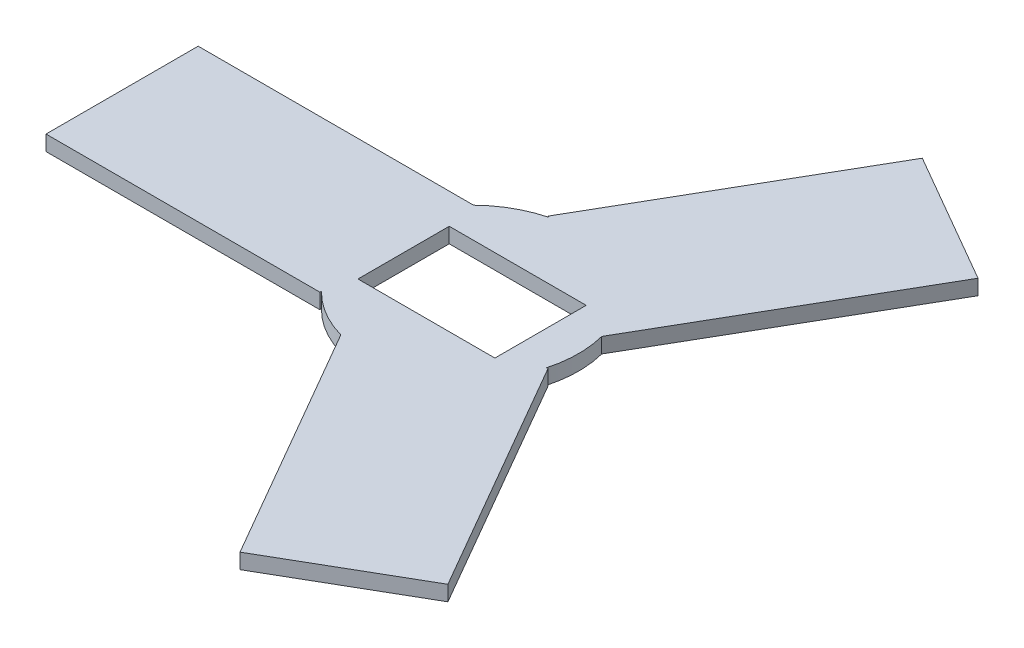
SolidWorks part; units mm, degrees
ref_plane "Plan de face" through (0, 0, 0) normal (0, 0, 1) x (1, 0, 0)
ref_plane "Plan de dessus" through (0, 0, 0) normal (0, 1, 0) x (1, 0, 0)
ref_plane "Plan de droite" through (0, 0, 0) normal (1, 0, 0) x (0, 0, -1)
sketch "Esquisse3" plane through (0, 0, 0) normal (0, 1, 0) x (1, 0, 0)
  line L0 (-150.1573, 0) -> (189.6273, 0) construction
  line L1 (-83.8395, -145.9242) -> (87.7229, 151.2306) construction
  line L2 (-78.0725, 135.2255) -> (117.7517, -203.9519) construction
  line L3 (-125, 131.2995) -> (-125, -153.5705) construction
  line L4 (-25, -25) -> (-115, -25)
  line L6 (-25, 25) -> (-24.4949, 25)
  line L7 (-115, -25) -> (-115, 25)
  line L8 (-25, -25) -> (-115, 25) construction
  line L9 (-25, 25) -> (-115, -25) construction
  line L10 (-24.4949, 25) -> (-115, 25)
  line L11 (33.8981, 8.7132) -> (79.1506, 87.0929)
  line L12 (35.8494, 112.0929) -> (79.1506, 87.0929)
  line L13 (-9.1506, 34.1506) -> (35.8494, 112.0929)
  line L14 (-9.4032, -33.7132) -> (35.8494, -112.0929)
  line L15 (79.1506, -87.0929) -> (35.8494, -112.0929)
  line L16 (34.1506, -9.1506) -> (79.1506, -87.0929)
  line L17 (-24.4949, 25) -> (-25, -25)
  line L18 (-9.1506, 34.1506) -> (33.8981, 8.7132)
  line L19 (-9.4032, -33.7132) -> (34.1506, -9.1506)
  circle A0 centre (0, 0) radius 125
  circle A1 centre (0, 0) radius 35
  circle A2 centre (0, 0) radius 125
  circle A3 centre (0, 0) radius 125
  point P9 (-70, 0)
  point P32 (0, 0)
  dimension "D1" = 250
  dimension "D4" = 70
  dimension "D2" = 120
  dimension "D3" = 120
  dimension "D5" = 10
  dimension "D6" = 50
  dimension "D7" = 90
  dimension "D8" = 3
extrude "Boss.-Extru.3" add sketch "Esquisse3" along normal blind 5 contours A1 L6 L10 L7 L4 L17 | A1 L14 L15 L16 L19 | L19 A1 L18 L17 | A1 L11 L12 L13 L18 | L18 A1
sketch "Esquisse4" plane through (0, 5, 0) normal (0, 1, 0) x (1, 0, 0)
  line L1 (22.5, -15) -> (-22.5, -15)
  line L2 (22.5, -15) -> (22.5, 15)
  line L3 (22.5, 15) -> (-22.5, 15)
  line L4 (-22.5, -15) -> (-22.5, 15)
  line L5 (22.5, -15) -> (-22.5, 15) construction
  line L6 (22.5, 15) -> (-22.5, -15) construction
  point P0 (0, 0)
  dimension "D1" = 45
  dimension "D2" = 30
extrude "Enlèv. mat.-Extru.1" cut sketch "Esquisse4" against normal through all
